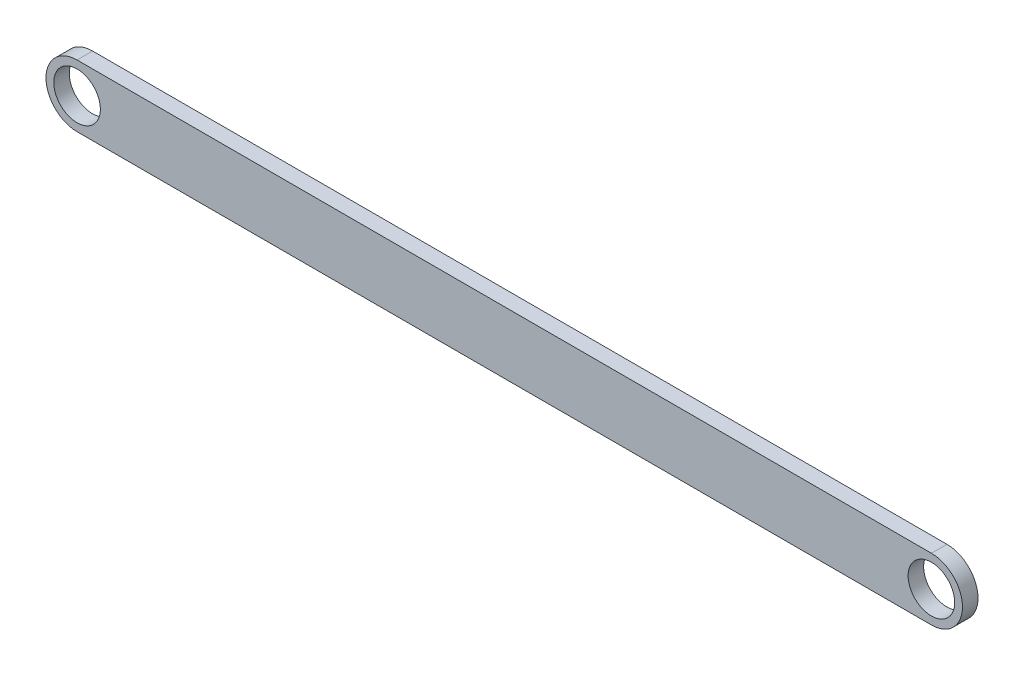
SolidWorks part; units mm, degrees
ref_plane "Спереди" through (0, 0, 0) normal (0, 0, 1) x (1, 0, 0)
ref_plane "Сверху" through (0, 0, 0) normal (0, 1, 0) x (1, 0, 0)
ref_plane "Справа" through (0, 0, 0) normal (1, 0, 0) x (0, 0, -1)
other "Configuration Table"
sketch "Эскиз1" plane through (0, 0, 0) normal (0, 0, 1) x (1, 0, 0)
  line L0 (0, 0) -> (550, 0) construction
  line L1 (0, 20) -> (550, 20)
  line L2 (0, -20) -> (550, -20)
  arc A0 (0, 20) -> (0, -20) centre (0, 0) ccw
  arc A1 (550, -20) -> (550, 20) centre (550, 0) ccw
  circle A2 centre (0, 0) radius 15
  circle A3 centre (550, 0) radius 15
  point P3 (275, 0)
  dimension "D3" = 30
  dimension "D4" = 30
  dimension "D1" = 550
  dimension "D2" = 40
extrude "Бобышка-Вытянуть3" add sketch "Эскиз1" along normal blind 10
